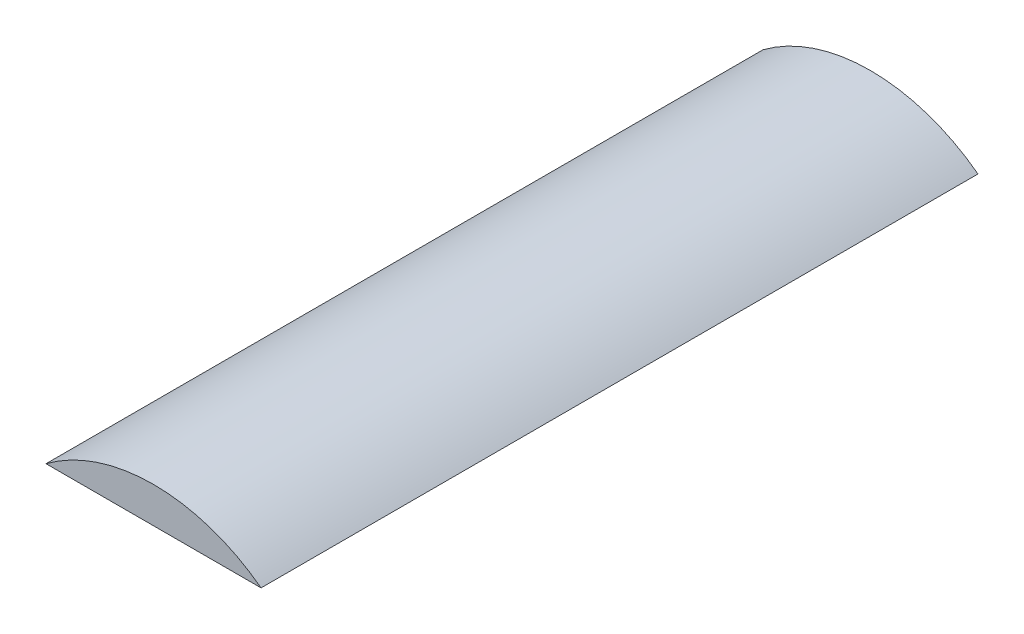
SolidWorks part; units mm, degrees
ref_plane "Front Plane" through (0, 0, 0) normal (0, 0, 1) x (1, 0, 0)
ref_plane "Top Plane" through (0, 0, 0) normal (0, 1, 0) x (1, 0, 0)
ref_plane "Right Plane" through (0, 0, 0) normal (1, 0, 0) x (0, 0, -1)
sketch "Sketch1" plane through (0, 0, 0) normal (0, 0, 1) x (1, 0, 0)
  line L2 (-1.5, 2) -> (1.5, 2)
  arc A2 (1.5, 2) -> (-1.5, 2) centre (0, 0) ccw
extrude "Boss-Extrude1" add sketch "Sketch1" along normal blind 10
